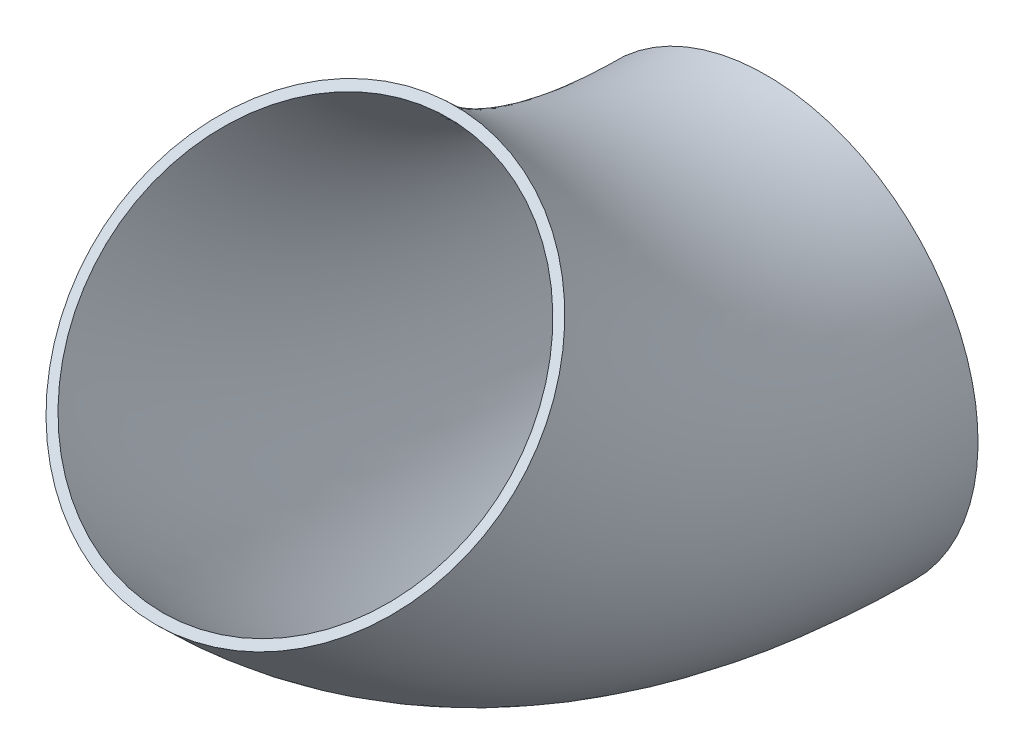
SolidWorks part; units mm, degrees
ref_plane "Plan de face" through (0, 0, 0) normal (0, 0, 1) x (1, 0, 0)
ref_plane "Plan de dessus" through (0, 0, 0) normal (0, 1, 0) x (1, 0, 0)
ref_plane "Plan de droite" through (0, 0, 0) normal (1, 0, 0) x (0, 0, -1)
sketch "Esquisse1" plane through (0, 0, 0) normal (0, 0, 1) x (1, 0, 0)
  line L0 (0, -35.75) -> (0, 35.75) construction
  circle A0 centre (0, 0) radius 32.5
  circle A1 centre (0, 0) radius 31
  dimension "D1" = 65
  dimension "D2" = 62
sketch "Esquisse2" plane through (0, 0, 0) normal (1, 0, 0) x (0, 0, -1)
  line L0 (0, 0) -> (0, 100) construction
  line L1 (0, 100) -> (-70.7107, 29.2893) construction
  arc A0 (0, 0) -> (-70.7107, 29.2893) centre (0, 100) cw
  dimension "D1" = 45
  dimension "D2" = 100
sweep "Balayage5" add profiles "Esquisse1" path "Esquisse2"
